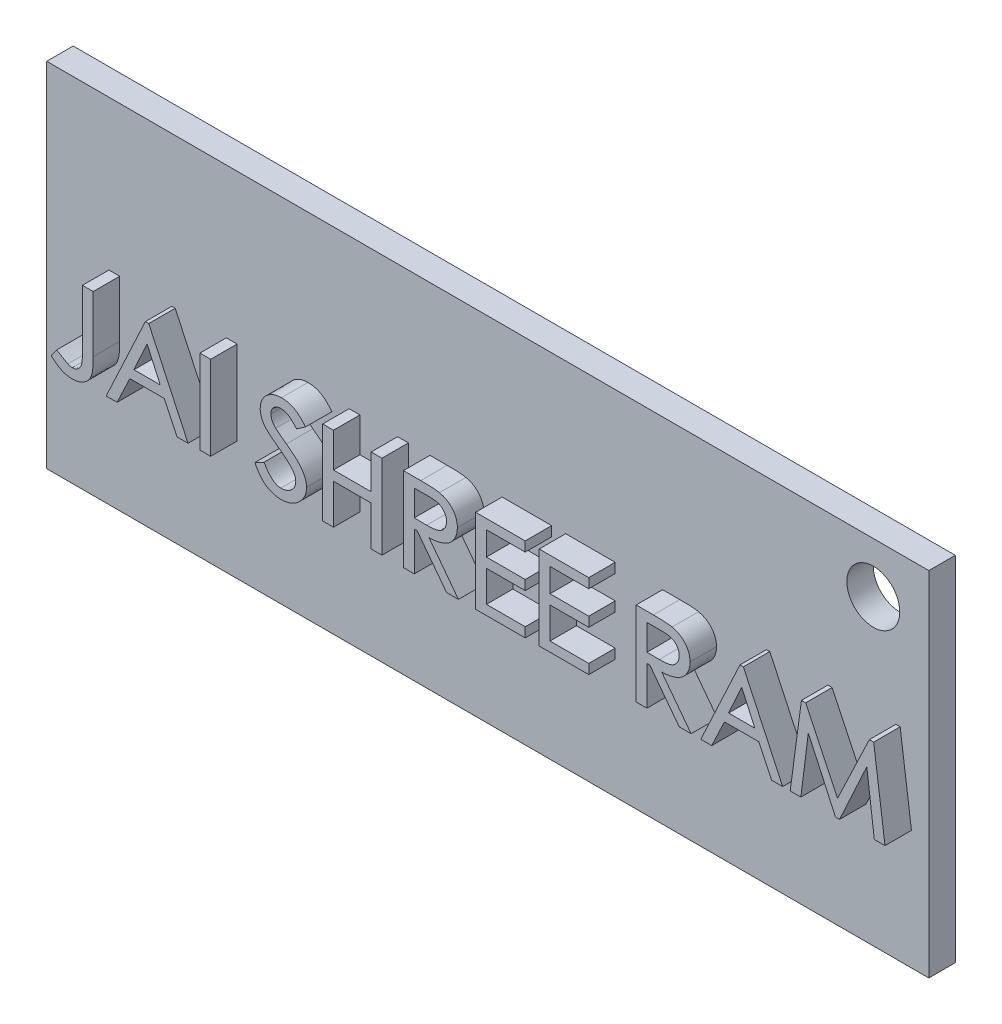
SolidWorks part; units mm, degrees
ref_plane "Front Plane" through (0, 0, 0) normal (0, 0, 1) x (1, 0, 0)
ref_plane "Top Plane" through (0, 0, 0) normal (0, 1, 0) x (1, 0, 0)
ref_plane "Right Plane" through (0, 0, 0) normal (1, 0, 0) x (0, 0, -1)
sketch "Sketch1" plane through (0, 0, 0) normal (0, 0, 1) x (1, 0, 0)
  line L1 (0, 0) -> (50, 0)
  line L2 (0, 0) -> (0, 20)
  line L3 (0, 20) -> (50, 20)
  line L4 (50, 0) -> (50, 20)
  dimension "D1" = 20
  dimension "D2" = 50
extrude "Boss-Extrude1" add sketch "Sketch1" along normal blind 2
sketch "Sketch2" plane through (0, 0, 2) normal (0, 0, 1) x (1, 0, 0)
  text T0 "JAI SHREE RAM" font "Century Gothic" height in points 18
extrude "Boss-Extrude2" add sketch "Sketch2" along normal blind 1.5
sketch "Sketch3" plane through (0, 0, 2) normal (0, 0, 1) x (1, 0, 0)
  circle A0 centre (46.8537, 17.1429) radius 1.5
  dimension "D1" = 3
extrude "Cut-Extrude1" cut sketch "Sketch3" against normal blind 4.5
sketch "Sketch4" plane through (0, 0, 0) normal (0, 0, -1) x (-1, 0, 0)
  line L1 (-50, 0) -> (0, 0)
  line L2 (-50, 0) -> (-50, 20)
  line L3 (-50, 20) -> (0, 20)
  line L4 (0, 0) -> (0, 20)
extrude "Cut-Extrude2" cut sketch "Sketch4" against normal blind 0.5
